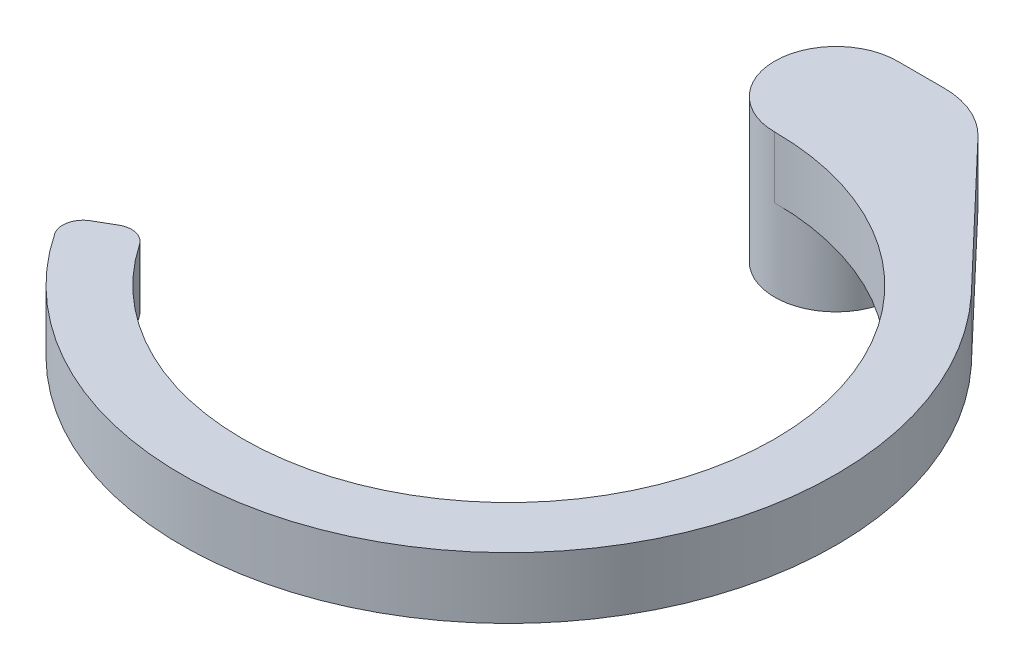
SolidWorks part; units mm, degrees
ref_plane "正面" through (0, 0, 0) normal (0, 0, 1) x (1, 0, 0)
ref_plane "平面" through (0, 0, 0) normal (0, 1, 0) x (1, 0, 0)
ref_plane "右側面" through (0, 0, 0) normal (1, 0, 0) x (0, 0, -1)
sketch "ｽｹｯﾁ2" plane through (0, 0, 0) normal (0, 1, 0) x (1, 0, 0)
  line L1 (-1.8089, 2.6033) -> (0, 0)
  line L2 (-60.4669, -34.9106) -> (-64.8074, -37.4166)
  line L4 (0, 95) -> (11.4274, 95)
  line L5 (25.9115, 88.7917) -> (58.5757, 54.4875)
  arc A0 (-66.4612, -44.5298) -> (57.2894, 55.8384) centre (0, 0) ccw
  arc A1 (-53.8264, -36.4378) -> (0, 65) centre (0, 0) ccw
  arc A2 (0, 95) -> (0, 65) centre (0, 80) ccw
  arc A3 (11.4274, 95) -> (25.9115, 88.7917) centre (11.4274, 75) cw
  arc A4 (-53.8264, -36.4378) -> (-60.4669, -34.9106) centre (-57.9669, -39.2407) ccw
  arc A5 (-66.4612, -44.5298) -> (-64.8074, -37.4166) centre (-62.3074, -41.7467) cw
  dimension "D1" = 160
  dimension "D2" = 130
  dimension "D4" = 20
  dimension "D5" = 5
  dimension "D6" = 5
extrude "ﾎﾞｽ - 押し出し4" add sketch "ｽｹｯﾁ2" along normal blind 15 contours A5 A0 L5 A3 L4 A2 A1 A4 L2
sketch "ｽｹｯﾁ4" plane through (0, 0, 0) normal (0, -1, 0) x (1, 0, 0)
  circle A0 centre (0, -80) radius 15
  dimension "D1" = 30
extrude "ﾎﾞｽ - 押し出し5" add sketch "ｽｹｯﾁ4" along normal blind 20
sketch "ｽｹｯﾁ5" plane through (0, -20, 0) normal (0, -1, 0) x (-1, 0, 0)
  circle A0 centre (0, 80) radius 10
  dimension "D1" = 20
extrude "ｶｯﾄ - 押し出し1" cut sketch "ｽｹｯﾁ5" against normal blind 2
